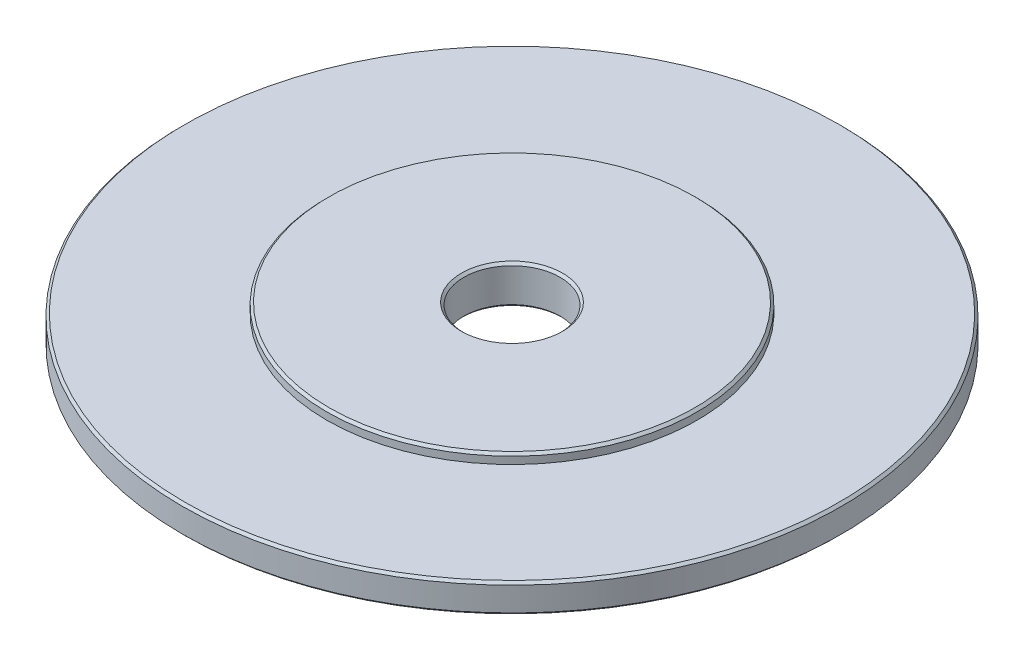
SolidWorks part; units mm, degrees
material "POM 乙缩醛共聚物"
ref_plane "前视基准面" through (0, 0, 0) normal (0, 0, 1) x (1, 0, 0)
ref_plane "上视基准面" through (0, 0, 0) normal (0, 1, 0) x (1, 0, 0)
ref_plane "右视基准面" through (0, 0, 0) normal (1, 0, 0) x (0, 0, -1)
sketch "草图2" plane through (0, 0, 0) normal (1, 0, 0) x (0, 0, -1)
  line L0 (10, 0) -> (68.5, 0)
  line L1 (68.5, 0) -> (68.5, 6)
  line L2 (68.5, 6) -> (38.5, 6)
  line L3 (38.5, 6) -> (38.5, 8)
  line L4 (38.5, 8) -> (10, 8)
  line L5 (10, 8) -> (10, 0)
  line L6 (0, 0) -> (0, 76.2211) construction
  dimension "D1" = 6
  dimension "D2" = 38.5
  dimension "D3" = 2
  dimension "D4" = 30
  dimension "D5" = 10
revolve "旋转1" add sketch "草图2" angle 360 about L6
chamfer "倒角1" distance 0.5 angle 45 5 edges at (0, 0, -68.5) (0, 6, -68.5) (0, 8, -10) (0, 0, -10) (0, 8, -38.5)
